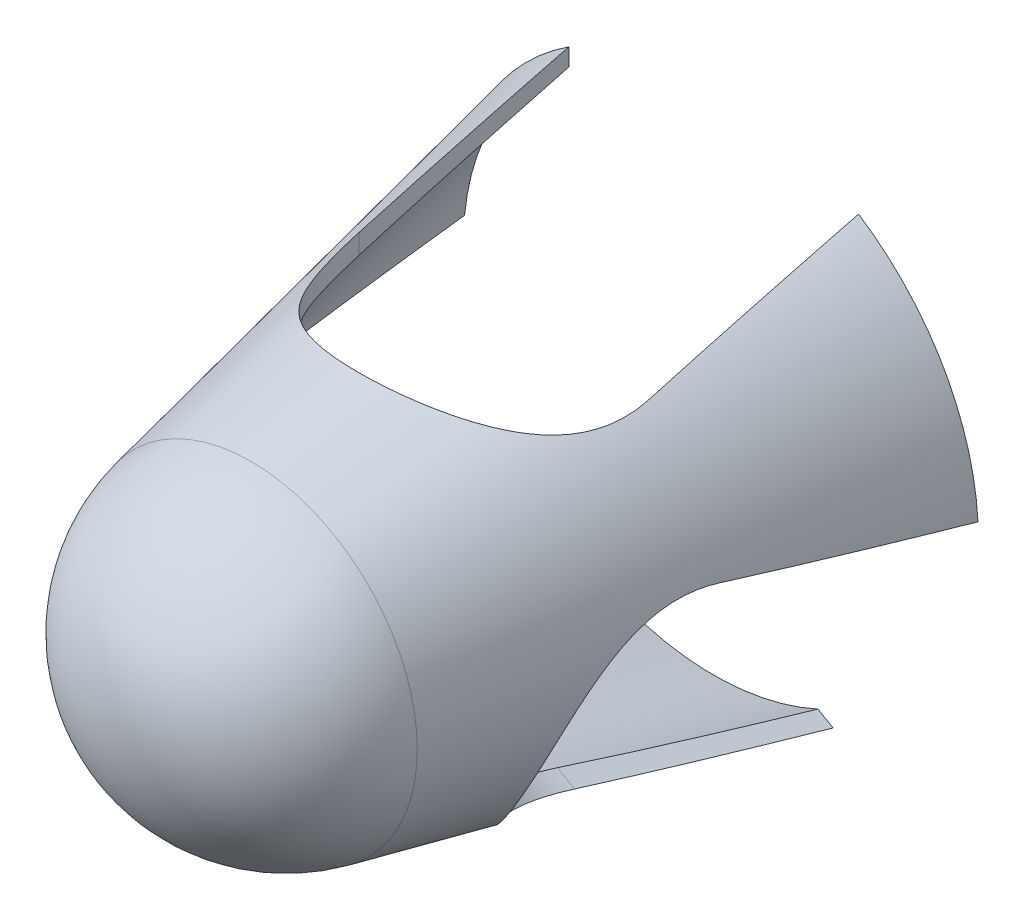
SolidWorks part; units mm, degrees
ref_plane "Ebene vorne" through (0, 0, 0) normal (0, 0, 1) x (1, 0, 0)
ref_plane "Ebene oben" through (0, 0, 0) normal (0, 1, 0) x (1, 0, 0)
ref_plane "Ebene rechts" through (0, 0, 0) normal (1, 0, 0) x (0, 0, -1)
sketch "Skizze1" plane through (0, 0, 0) normal (1, 0, 0) x (0, 0, -1)
  line L0 (2900, -3654.0837) -> (2900, 0) construction
  line L1 (-3000, 2000) -> (3000, 2000) construction
  line L2 (-3000, 2000) -> (-3000, -2000) construction
  line L3 (-3000, -2000) -> (3000, -2000) construction
  line L4 (3000, 2000) -> (3000, -2000) construction
  line L6 (2900, -3654.0837) -> (-3488.084, -2296.2545)
  line L7 (-3000, 0) -> (-3000, -2200)
  line L8 (-3000, -2200) -> (2900, -3454.0837)
  line L9 (0, 0) -> (-3960.7907, 0) construction
  line L10 (0, 0) -> (4818.5589, 0) construction
  line L11 (-5347.5542, 0) -> (-3000, 0)
  line L12 (2900, -3454.0837) -> (2900, -3654.0837)
  arc A1 (-3488.084, -2296.2545) -> (-5347.5542, 0) centre (-3000, 0) cw
  point P8 (0, 2000)
  point P16 (3000, 0)
  dimension "D1" = 6000
  dimension "D2" = 4000
  dimension "D3" = 200
  dimension "D6" = 200
  dimension "D7" = 12
  dimension "D8" = 100
  dimension "D9" = 12
revolve "Rotation1" add sketch "Skizze1" angle 360 about L10
sketch "Skizze2" plane through (0, 0, 0) normal (0, 1, 0) x (1, 0, 0)
  line L0 (-2000, 0) -> (-2000, 2900)
  line L1 (3454.0837, 2900) -> (-3454.0837, 2900) construction
  line L2 (-2000, 2900) -> (2000, 2900)
  line L3 (2000, 2900) -> (2000, 0)
  arc A1 (-2000, 0) -> (2000, 0) centre (0, 0) ccw
  dimension "D1" = 2000
extrude "Schnitt-Linear austragen1" cut sketch "Skizze2" along normal through all contours L2 L3 A1 L0
pattern_circular "Kreismuster1" count 3 over 360 about axis through (0, 0, 0) along (0, 0, 1) of "Schnitt-Linear austragen1"
